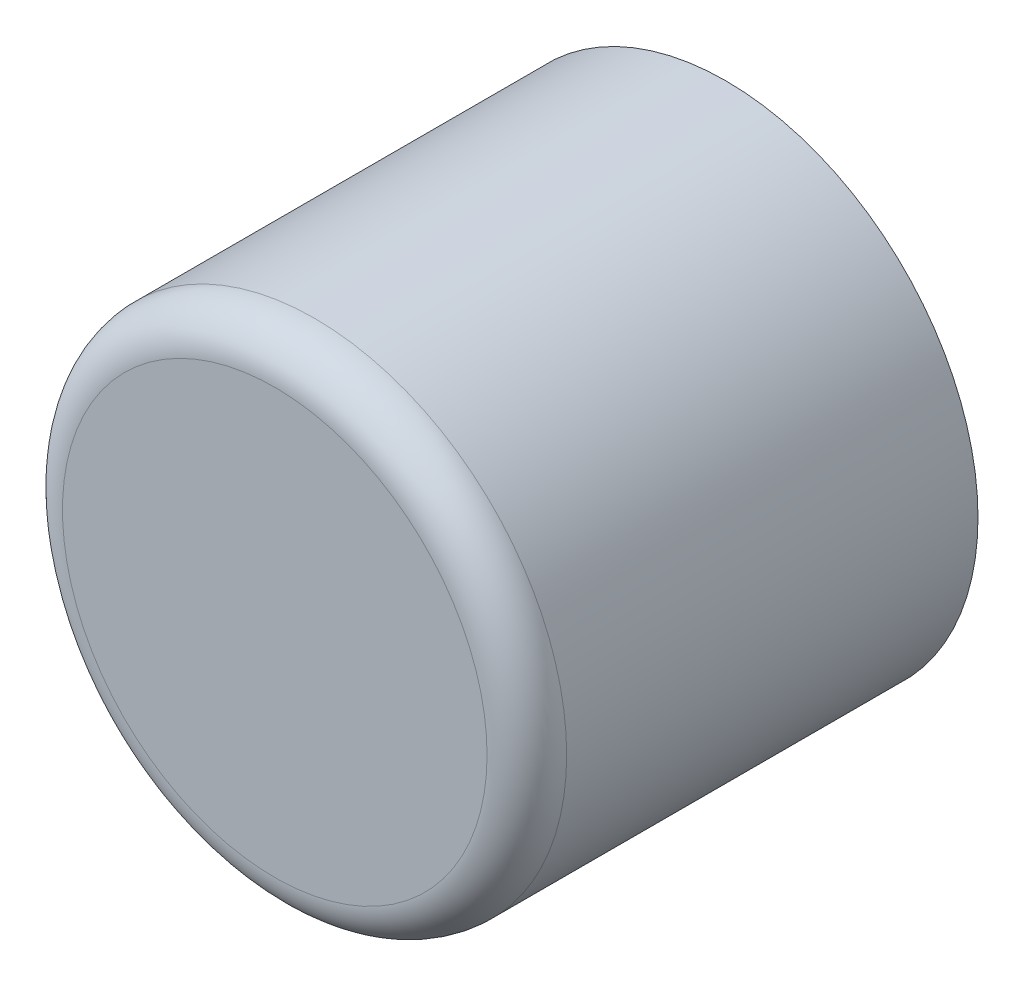
SolidWorks part; units mm, degrees
material "镀铬不锈钢"
ref_plane "前视基准面" through (0, 0, 0) normal (0, 0, 1) x (1, 0, 0)
ref_plane "上视基准面" through (0, 0, 0) normal (0, 1, 0) x (1, 0, 0)
ref_plane "右视基准面" through (0, 0, 0) normal (1, 0, 0) x (0, 0, -1)
sketch "草图1" plane through (0, 0, 0) normal (0, 0, 1) x (1, 0, 0)
  circle A0 centre (0, 0) radius 19
  dimension "D1" = 38
extrude "凸台-拉伸1" add sketch "草图1" along normal blind 34
fillet "圆角1" radius 3 1 edges at (19, 0, 34)
